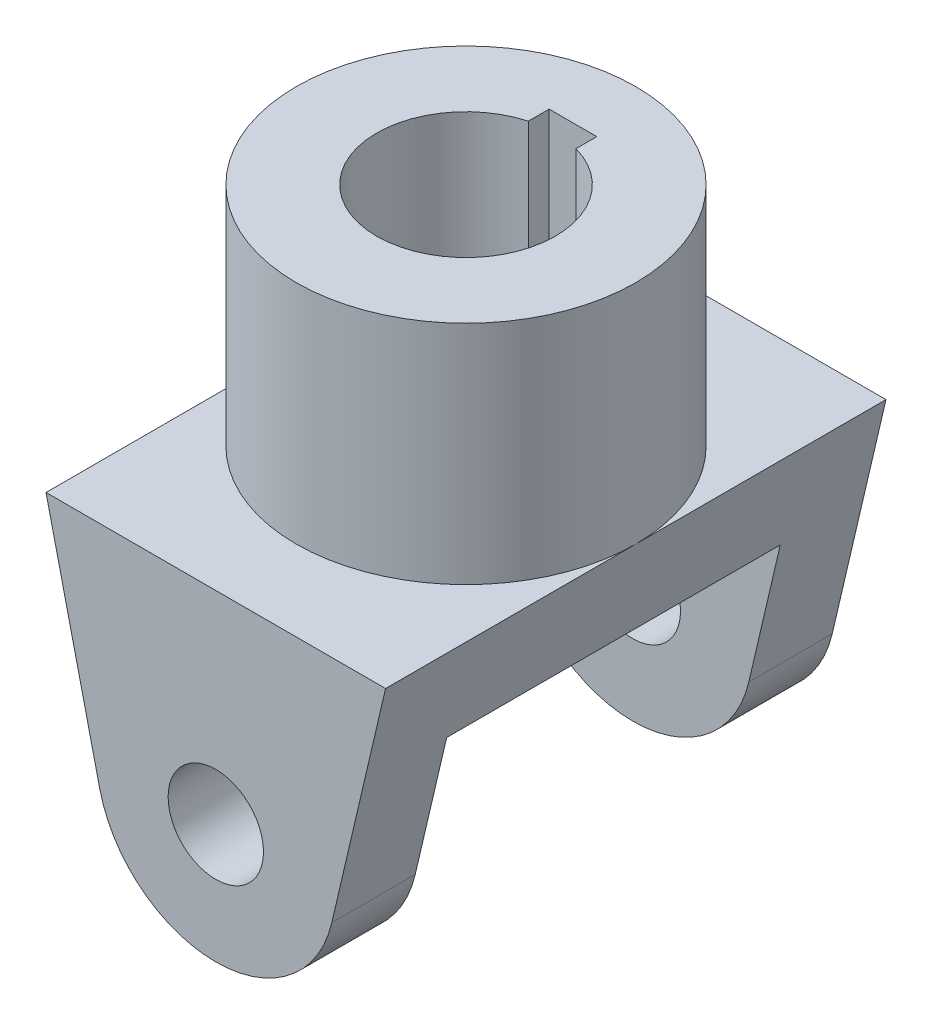
SolidWorks part; units mm, degrees
material "Cast Carbon Steel"
ref_plane "Front Plane" through (0, 0, 0) normal (0, 0, 1) x (1, 0, 0)
ref_plane "Top Plane" through (0, 0, 0) normal (0, 1, 0) x (1, 0, 0)
ref_plane "Right Plane" through (0, 0, 0) normal (1, 0, 0) x (0, 0, -1)
sketch "Sketch1" plane through (0, 0, 0) normal (0, 1, 0) x (1, 0, 0)
  circle A0 centre (0, 0) radius 28.5
  circle A1 centre (0, 0) radius 15
extrude "Boss-Extrude1" add sketch "Sketch1" along normal blind 38
sketch "Sketch2" plane through (0, 0, 0) normal (0, -1, 0) x (1, 0, 0)
  line L1 (28.5, 42) -> (-28.5, 42)
  line L2 (28.5, 42) -> (28.5, -42)
  line L3 (28.5, -42) -> (-28.5, -42)
  line L4 (-28.5, 42) -> (-28.5, -42)
  line L5 (28.5, 42) -> (-28.5, -42) construction
  line L6 (28.5, -42) -> (-28.5, 42) construction
  point P0 (0, 0)
extrude "Boss-Extrude2" add sketch "Sketch2" along normal blind 16
sketch "Sketch6" plane through (0, 0, 42) normal (0, 0, 1) x (1, 0, 0)
  line L1 (-28.5, -16) -> (28.5, -16)
  line L2 (-28.5, -16) -> (-28.5, -54)
  line L3 (-28.5, -54) -> (28.5, -54)
  line L4 (28.5, -16) -> (28.5, -54)
extrude "Boss-Extrude4" add sketch "Sketch6" against normal blind 14
ref_plane "Plane2" through (0, 0, 0) normal (0, 0, 1) x (1, 0, 0)
sketch "Sketch7" plane through (0, 0, -42) normal (0, 0, -1) x (-1, 0, 0)
  line L1 (-28.5, -16) -> (28.5, -16)
  line L2 (-28.5, -16) -> (-28.5, -54)
  line L3 (-28.5, -54) -> (28.5, -54)
  line L4 (28.5, -16) -> (28.5, -54)
extrude "Boss-Extrude5" add sketch "Sketch7" against normal blind 14
sketch "Sketch8" plane through (0, 0, -42) normal (0, 0, -1) x (-1, 0, 0)
  line L0 (0, 38) -> (0, -34) construction
  line L1 (28.5, 38) -> (-28.5, 38) construction
  line L2 (28.5, 0) -> (-28.5, 0) construction
  circle A0 centre (0, -34) radius 8
  dimension "D1" = 34
extrude "Cut-Extrude3" cut sketch "Sketch8" against normal through all
sketch "Sketch9" plane through (0, 0, 42) normal (0, 0, 1) x (1, 0, 0)
  line L0 (-28.5, 0) -> (-19.4735, -38.5587)
  line L2 (28.5, 0) -> (19.4735, -38.5587)
  line L3 (-28.5, 0) -> (-28.5, -54)
  line L4 (-28.5, -54) -> (28.5, -54)
  line L5 (28.5, -54) -> (28.5, 0)
  arc A0 (-19.4735, -38.5587) -> (19.4735, -38.5587) centre (0, -34) ccw
  line M3 (-28.5, 0) -> (-28.5, -54)
  line M4 (-28.5, -54) -> (28.5, -54)
  line M5 (28.5, -54) -> (28.5, 0)
extrude "Cut-Extrude4" cut sketch "Sketch9" against normal through all contours A0 L0 M3 M4 | A0 L4 L2 M5
sketch "Sketch10" plane through (0, 38, 0) normal (0, 1, 0) x (1, 0, 0)
  line L0 (0, 15) -> (0, 0) construction
  circle A0 centre (0, 0) radius 15 construction
  circle A1 centre (0, 0) radius 15 construction
ref_plane "Plane3" through (0, 38, -15) normal (0, 0, 1) x (1, 0, 0)
sketch "Sketch11" plane through (0, 38, 0) normal (0, 1, 0) x (1, 0, 0)
  line L1 (-4, 17.9568) -> (4, 17.9568)
  line L2 (-4, 17.9568) -> (-4, 14.4568)
  line L3 (4, 17.9568) -> (4, 14.4568)
  line L6 (0, 15) -> (0, 17.9568) construction
  arc A0 (4, 14.4568) -> (-4, 14.4568) centre (0, 0) ccw
  circle A1 centre (0, 0) radius 15 construction
  dimension "D1" = 3.5
extrude "Cut-Extrude5" cut sketch "Sketch11" against normal blind 38
